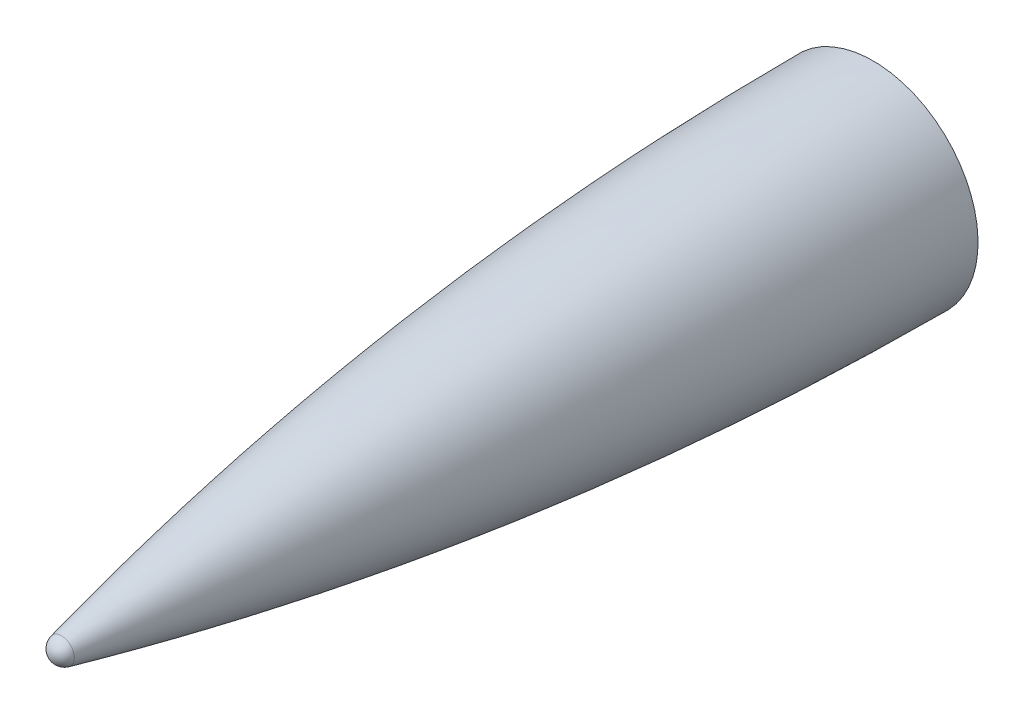
SolidWorks part; units mm, degrees
ref_plane "Front Plane" through (0, 0, 0) normal (0, 0, 1) x (1, 0, 0)
ref_plane "Top Plane" through (0, 0, 0) normal (0, 1, 0) x (1, 0, 0)
ref_plane "Right Plane" through (0, 0, 0) normal (1, 0, 0) x (0, 0, -1)
sketch "Unblunted Reference" plane through (0, 0, 0) normal (1, 0, 0) x (0, 0, -1)
  line L2 (0, 0) -> (-561.5876, 0) construction
  line L3 (0, 0) -> (0, 50.8) construction
  arc A1 (-385.322, 0) -> (-398.022, 0) centre (-391.672, 0) ccw construction
  spline S0 degree 4 poles (-459.753, -10.5198) (-458.8979, -10.2876) (-457.188, -9.8245) (-454.6259, -9.1341) (-451.1978, -8.2181) (-446.9606, -7.0946) (-442.7021, -5.9783) (-438.5157, -4.8918) (-434.2469, -3.7972) (-430.9886, -2.9671) (-427.3742, -2.0565) (-424.5079, -1.3371) (-420.2908, -0.2927) (-418.3417, 0.1872) (-415.2679, 0.939) (-413.1135, 1.4623) (-411.0374, 1.964) (-408.2622, 2.6314) (-404.3783, 3.5579) (-400.1738, 4.5483) (-395.9226, 5.5377) (-391.6512, 6.5217) (-387.341, 7.5045) (-382.3125, 8.6363) (-375.1216, 10.2294) (-366.485, 12.1023) (-357.8374, 13.9269) (-349.1801, 15.7031) (-341.959, 17.1509) (-336.1783, 18.2897) (-330.3938, 19.4091) (-324.6056, 20.5091) (-317.3658, 21.8597) (-305.7724, 23.9689) (-269.4922, 30.276) (-211.1797, 38.8064) (-152.5404, 44.8505) (-95.1967, 48.4336) (-62.816, 49.6937) (-52.5106, 50.0254) (-43.676, 50.2603) (-37.7858, 50.3971) (-32.6315, 50.4995) (-28.2133, 50.5749) (-24.5472, 50.6293) (-21.6333, 50.6676) (-18.7349, 50.7009) (-15.8532, 50.7294) (-12.9736, 50.753) (-10.0727, 50.772) (-7.2352, 50.7862) (-4.3734, 50.7957) (-0.7824, 50.8006) (1.2225, 50.8003) (5.5599, 50.7937) (8.5094, 50.78) (12.2323, 50.7594) (15.5816, 50.7319) (19.1128, 50.6975) (22.5547, 50.6563) (26.0564, 50.608) (29.5522, 50.5525) (33.0747, 50.4897) (36.6075, 50.4195) (39.2594, 50.3614) (41.0265, 50.3204) (41.9099, 50.2993) knots 0 0 0 0 0 0.006985 0.01397 0.020955 0.02794 0.041657 0.048516 0.055375 0.062233 0.069092 0.075951 0.08281 0.088494 0.094178 0.09702 0.099862 0.105546 0.116914 0.128282 0.134092 0.139901 0.151519 0.163138 0.174757 0.197994 0.221231 0.23285 0.244468 0.256087 0.267706 0.279324 0.290943 0.31418 0.360654 0.569789 0.755687 0.778924 0.81378 0.825399 0.837017 0.848636 0.860254 0.866064 0.871873 0.877557 0.883241 0.888925 0.894609 0.900293 0.905978 0.911662 0.917346 0.924192 0.931037 0.937883 0.944729 0.951575 0.958421 0.965267 0.972113 0.979084 0.986056 0.993028 1 1 1 1 1 construction
  spline S1 degree 4 poles (-419.1, 0) (-418.516, 0.1437) (-417.3411, 0.432) (-415.2679, 0.939) (-413.1135, 1.4623) (-411.0374, 1.964) (-408.2622, 2.6314) (-404.3783, 3.5579) (-400.1738, 4.5483) (-395.9226, 5.5377) (-391.6512, 6.5217) (-387.341, 7.5045) (-382.3125, 8.6363) (-375.1216, 10.2294) (-366.485, 12.1023) (-357.8374, 13.9269) (-349.1801, 15.7031) (-341.959, 17.1509) (-336.1783, 18.2897) (-330.3938, 19.4091) (-324.6056, 20.5091) (-317.3658, 21.8597) (-305.7724, 23.9689) (-269.4922, 30.276) (-211.1797, 38.8064) (-152.5404, 44.8505) (-95.1967, 48.4336) (-62.816, 49.6937) (-52.5106, 50.0254) (-43.676, 50.2603) (-37.7858, 50.3971) (-32.6315, 50.4995) (-28.2133, 50.5749) (-24.5472, 50.6293) (-21.6333, 50.6676) (-18.7349, 50.7009) (-15.8532, 50.7294) (-12.9736, 50.753) (-10.0727, 50.772) (-7.2352, 50.7862) (-4.3734, 50.7957) (-1.8111, 50.7992) (-0.6014, 50.8) (0, 50.8) knots 0.08281 0.08281 0.08281 0.08281 0.08281 0.088494 0.094178 0.09702 0.099862 0.105546 0.116914 0.128282 0.134092 0.139901 0.151519 0.163138 0.174757 0.197994 0.221231 0.23285 0.244468 0.256087 0.267706 0.279324 0.290943 0.31418 0.360654 0.569789 0.755687 0.778924 0.81378 0.825399 0.837017 0.848636 0.860254 0.866064 0.871873 0.877557 0.883241 0.888925 0.894609 0.900293 0.905978 0.911662 0.917346 0.917346 0.917346 0.917346 0.917346
  point P8 (-393.0949, 6.1885)
  point P9 (0, 0)
  point P10 (0, 0)
  dimension "D2" = 6.35
  dimension "D1" = 50.8
sketch "Sketch2" plane through (0, 0, 0) normal (1, 0, 0) x (0, 0, -1)
  line L0 (0, 0) -> (0, 50.8)
  line L1 (0, 0) -> (-461.8494, 0) construction
  line L2 (-419.1, 20.3837) -> (-419.1, -20.3837) construction
  line L3 (-398.022, 0) -> (0, 0)
  arc A0 (-393.095, 6.1885) -> (-398.022, 0) centre (-391.672, 0) ccw
  arc A1 (-385.322, 0) -> (-393.095, 6.1885) centre (-391.672, 0) ccw construction
  spline S0 degree 4 poles (-431.6185, -3.1289) (-431.0154, -2.9758) (-429.8036, -2.6689) (-427.3957, -2.0611) (-423.7557, -1.1502) (-419.543, -0.1058) (-414.6866, 1.0826) (-409.917, 2.2364) (-405.6376, 3.2578) (-402.1583, 4.0809) (-398.9748, 4.8262) (-396.945, 5.3) (-393.8534, 6.0144) (-392.403, 6.3479) (-388.822, 7.1672) (-385.7644, 7.8589) (-381.5113, 8.814) (-375.8789, 10.0602) (-370.0306, 11.3344) (-364.3088, 12.5578) (-357.3562, 14.0196) (-350.4386, 15.4474) (-343.4871, 16.8503) (-336.5479, 18.2179) (-330.7521, 19.3389) (-326.1173, 20.2222) (-317.9989, 21.747) (-306.3911, 23.8625) (-293.603, 26.0866) (-279.6319, 28.3875) (-265.6445, 30.5882) (-251.6417, 32.6885) (-237.6204, 34.6631) (-223.5821, 36.5119) (-209.531, 38.2599) (-193.1237, 40.1815) (-176.6964, 41.9265) (-160.2514, 43.4946) (-146.1445, 44.7122) (-134.3834, 45.6636) (-122.6157, 46.5306) (-110.8421, 47.3132) (-96.7075, 48.1508) (-84.9239, 48.7643) (-73.1361, 49.2933) (-62.5242, 49.6932) (-55.4482, 49.9281) (-49.5514, 50.1027) (-44.8326, 50.2296) (-38.9361, 50.3725) (-33.0349, 50.4942) (-27.1405, 50.5947) (-21.8248, 50.6661) (-18.2956, 50.7058) (-15.3271, 50.7336) (-13.005, 50.7526) (-10.5727, 50.7685) (-8.3406, 50.7812) (-5.7598, 50.7907) (-3.7878, 50.7971) (-0.6994, 50.8003) (0.7749, 50.8003) (4.5572, 50.796) (7.7549, 50.7841) (12.323, 50.7603) (17.0436, 50.7194) (22.0649, 50.6646) (26.9213, 50.5958) (31.2978, 50.5233) (34.6635, 50.4583) (37.1532, 50.407) (38.3807, 50.3801) (38.9996, 50.3664) (39.3098, 50.3595) knots 0 0 0 0 0 0.005242 0.010484 0.020968 0.031452 0.041936 0.052295 0.062653 0.067832 0.073012 0.078191 0.08337 0.088334 0.093298 0.103226 0.113154 0.123081 0.142937 0.152865 0.162793 0.182648 0.202504 0.212432 0.22236 0.232287 0.242215 0.281927 0.321638 0.341494 0.361349 0.401061 0.440772 0.460627 0.480483 0.520194 0.579761 0.599617 0.619473 0.639328 0.67904 0.698895 0.718751 0.758462 0.778318 0.798174 0.808101 0.818029 0.827957 0.837885 0.857741 0.867668 0.877596 0.88256 0.887524 0.892488 0.897452 0.902416 0.90738 0.912344 0.917307 0.922444 0.927581 0.937855 0.948128 0.958402 0.968801 0.979201 0.9896 0.9948 0.9974 1 1 1 1 1 construction
  spline S1 degree 4 poles (-393.095, 6.1885) (-392.6155, 6.2988) (-391.6621, 6.5174) (-388.822, 7.1672) (-385.7644, 7.8589) (-381.5113, 8.814) (-375.8789, 10.0602) (-370.0306, 11.3344) (-364.3088, 12.5578) (-357.3562, 14.0196) (-350.4386, 15.4474) (-343.4871, 16.8503) (-336.5479, 18.2179) (-330.7521, 19.3389) (-326.1173, 20.2222) (-317.9989, 21.747) (-306.3911, 23.8625) (-293.603, 26.0866) (-279.6319, 28.3875) (-265.6445, 30.5882) (-251.6417, 32.6885) (-237.6204, 34.6631) (-223.5821, 36.5119) (-209.531, 38.2599) (-193.1237, 40.1815) (-176.6964, 41.9265) (-160.2514, 43.4946) (-146.1445, 44.7122) (-134.3834, 45.6636) (-122.6157, 46.5306) (-110.8421, 47.3132) (-96.7075, 48.1508) (-84.9239, 48.7643) (-73.1361, 49.2933) (-62.5242, 49.6932) (-55.4482, 49.9281) (-49.5514, 50.1027) (-44.8326, 50.2296) (-38.9361, 50.3725) (-33.0349, 50.4942) (-27.1405, 50.5947) (-21.8248, 50.6661) (-18.2956, 50.7058) (-15.3271, 50.7336) (-13.005, 50.7526) (-10.5727, 50.7685) (-8.3406, 50.7812) (-5.7598, 50.7907) (-3.7878, 50.7971) (-1.4915, 50.7995) (-0.492, 50.8) (0, 50.8) knots 0.08337 0.08337 0.08337 0.08337 0.08337 0.088334 0.093298 0.103226 0.113154 0.123081 0.142937 0.152865 0.162793 0.182648 0.202504 0.212432 0.22236 0.232287 0.242215 0.281927 0.321638 0.341494 0.361349 0.401061 0.440772 0.460627 0.480483 0.520194 0.579761 0.599617 0.619473 0.639328 0.67904 0.698895 0.718751 0.758462 0.778318 0.798174 0.808101 0.818029 0.827957 0.837885 0.857741 0.867668 0.877596 0.88256 0.887524 0.892488 0.897452 0.902416 0.90738 0.912344 0.917307 0.917307 0.917307 0.917307 0.917307
  point P8 (-419.1, 0)
  point P9 (-393.095, 6.1885)
  point P10 (0, 0)
  point P13 (0, 0)
  dimension "D1" = 50.8
  dimension "D5" = 6.35
  dimension "D2" = 419.1
  dimension "D3" = 26.005
  dimension "D4" = 6.1885
  dimension "D6" = 27.428
revolve "Revolve3" add sketch "Sketch2" angle 360 about L3
equation "\"R\"= 2'base radius"
equation "\"L\"= 16.5'overall length"
equation "\"rho\"= ( \"R\" ^ 2 + \"L\" ^ 2 ) / ( 2 * \"R\" )'ogive radius"
equation "\"rn\"= 0.25'spherical cap radius"
equation "\"xo\"= \"L\" - sqr ( ( \"rho\" - \"rn\" ) ^ 2 - ( \"rho\" - \"R\" ) ^ 2 )'spherical cap center (from origin)"
equation "\"yt\"= \"rn\" * ( \"rho\" - \"R\" ) / ( \"rho\" - \"rn\" )'tangency y-coordinate"
equation "\"xt\" = \"xo\" - sqr ( ( \"rn\" ^ 2 ) - ( \"yt\" ^ 2 ) )'tangency x-coordinate"
equation "\"xa\"= \"xo\" - \"rn\"'apex location (from origin)"
equation "\"D1@Unblunted Reference\" = \"R\""
equation "\"D2@Unblunted Reference\" = \"rn\""
equation "\"D1@Sketch2\"=\"R\""
equation "\"D2@Sketch2\"=\"L\""
equation "\"D3@Sketch2\"=\"xt\""
equation "\"D4@Sketch2\"=\"yt\""
equation "\"D5@Sketch2\"=\"rn\""
equation "\"D6@Sketch2\"=\"xo\""
